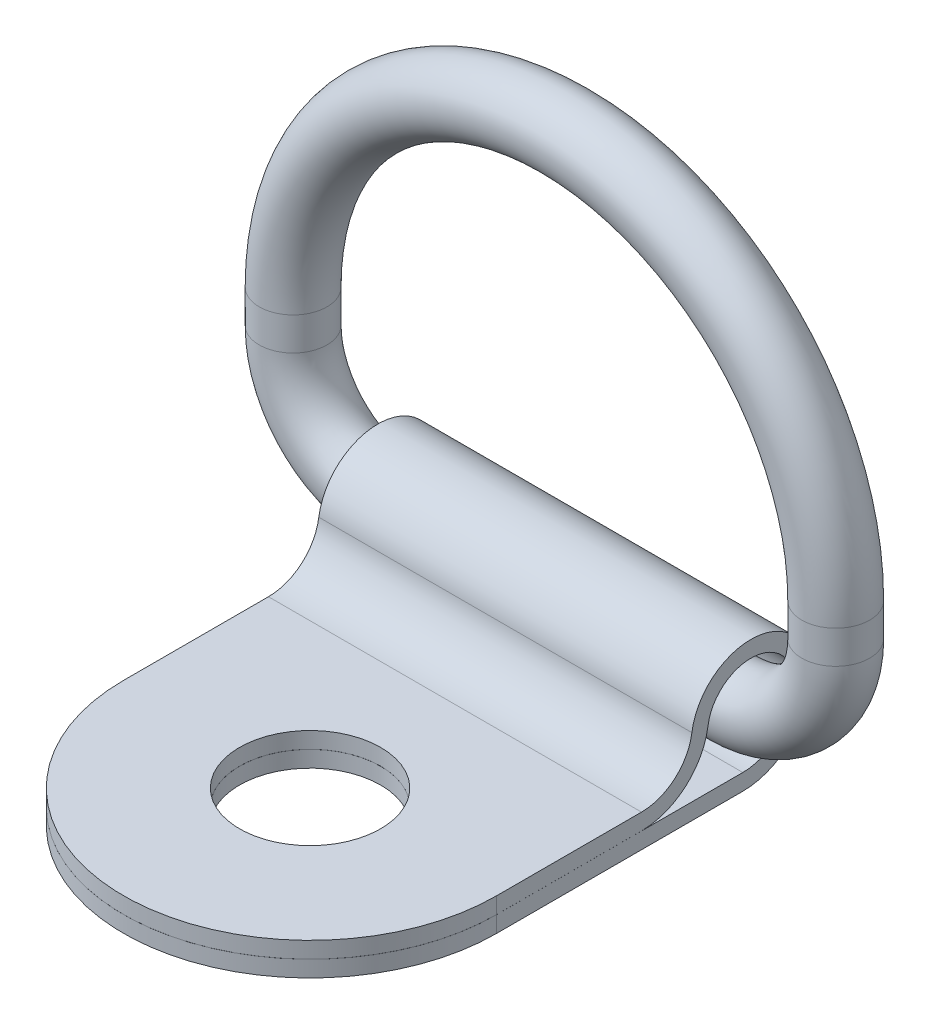
SolidWorks part; units mm, degrees
ref_plane "Front Plane" through (0, 0, 0) normal (0, 0, 1) x (1, 0, 0)
ref_plane "Top Plane" through (0, 0, 0) normal (0, 1, 0) x (1, 0, 0)
ref_plane "Right Plane" through (0, 0, 0) normal (1, 0, 0) x (0, 0, -1)
sketch "Sketch1" plane through (0, 0, 0) normal (0, 0, 1) x (1, 0, 0)
  line L0 (-7.8941, -1.5875) -> (7.8941, -1.5875) construction
  line L1 (0, 0) -> (0, 20.6375) construction
  line L2 (-14.2875, 6.35) -> (-14.2875, 4.8059) construction
  line L3 (-11.1125, 6.35) -> (-11.1125, 4.8059) construction
  line L4 (11.1125, 6.35) -> (11.1125, 4.8059) construction
  line L5 (14.2875, 6.35) -> (14.2875, 4.8059) construction
  line L6 (7.8941, 1.5875) -> (-7.8941, 1.5875) construction
  line L8 (0, 1.5875) -> (0, -1.5875) construction
  line L10 (-12.7, 6.35) -> (-12.7, 4.8059)
  line L11 (12.7, 6.35) -> (12.7, 4.8059)
  line L12 (-7.8941, 0) -> (7.8941, 0)
  arc A0 (14.2875, 6.35) -> (-14.2875, 6.35) centre (0, 6.35) ccw construction
  arc A1 (11.1125, 6.35) -> (-11.1125, 6.35) centre (0, 6.35) ccw construction
  circle A2 centre (0, 19.05) radius 1.5875 construction
  circle A3 centre (0, 0) radius 1.5875 construction
  arc A4 (12.7, 6.35) -> (-12.7, 6.35) centre (0, 6.35) ccw
  arc A5 (-7.8941, 0) -> (-12.7, 4.8059) centre (-7.8941, 4.8059) cw
  arc A6 (7.8941, 0) -> (12.7, 4.8059) centre (7.8941, 4.8059) ccw
  arc A7 (-7.8941, 1.5875) -> (-11.1125, 4.8059) centre (-7.8941, 4.8059) cw construction
  arc A8 (-7.8941, -1.5875) -> (-14.2875, 4.8059) centre (-7.8941, 4.8059) cw construction
  arc A9 (7.8941, -1.5875) -> (14.2875, 4.8059) centre (7.8941, 4.8059) ccw construction
  arc A10 (7.8941, 1.5875) -> (11.1125, 4.8059) centre (7.8941, 4.8059) ccw construction
  dimension "C" = 3.175
  dimension "A" = 22.225
  dimension "B" = 22.225
sketch "Sketch2" plane through (0, 0, 0) normal (1, 0, 0) x (0, 0, -1)
  circle A0 centre (0, 0) radius 1.5875
sweep "Sweep1" add profiles "Sketch2" path "Sketch1"
sketch "Sketch3" plane through (0, 0, 0) normal (1, 0, 0) x (0, 0, -1)
  line L0 (-20.6375, -3.175) -> (-0.381, -3.175)
  line L1 (-20.6375, -3.175) -> (-20.6375, -2.413)
  line L2 (-20.6375, -2.413) -> (-0.381, -2.413)
  line L4 (-20.6375, -2.4105) -> (-20.6375, -1.6485)
  line L5 (-20.6375, -1.6485) -> (-5.1231, -1.6485)
  line L6 (-20.6375, -2.4105) -> (-5.1231, -2.4105)
  line L7 (-11.9062, -3.175) -> (-11.9062, -2.413) construction
  circle A0 centre (0, 0) radius 2.032 construction
  arc A1 (-2.7658, 0.3956) -> (2.794, 0) centre (0, 0) cw
  arc A2 (-2.7658, 0.3956) -> (-5.1231, -1.6485) centre (-5.1231, 0.7328) cw
  arc A3 (-5.1231, -2.4105) -> (-2.0115, 0.2877) centre (-5.1231, 0.7328) ccw
  arc A4 (-2.0115, 0.2877) -> (2.032, 0) centre (0, 0) cw
  arc A5 (-0.381, -2.413) -> (2.032, 0) centre (-0.381, 0) ccw
  arc A6 (-0.381, -3.175) -> (2.794, 0) centre (-0.381, 0) ccw
  dimension "D1" = 4.064
  dimension "D6" = 2.3813
  dimension "D2" = 0.762
  dimension "D3" = 3.175
  dimension "D4" = 20.6375
  dimension "D7" = 0.0025
  dimension "D8" = 11.9062
extrude "Boss-Extrude1" add sketch "Sketch3" along normal mid plane 17.4625 separate body
sketch "Sketch4" plane through (0, -3.175, 0) normal (0, -1, 0) x (1, 0, 0)
  line L0 (-8.7312, 11.9062) -> (-8.7312, 20.6375)
  line L1 (-8.7312, 20.6375) -> (-8.7312, 21.9075)
  line L2 (-8.7312, 21.9075) -> (8.7313, 21.9075)
  line L3 (8.7313, 21.9075) -> (8.7312, 20.6375)
  line L4 (8.7312, 20.6375) -> (8.7312, 11.9062)
  line L5 (8.7312, 20.6375) -> (-8.7312, 20.6375) construction
  line L6 (8.7312, 5.1231) -> (8.7312, 20.6375) construction
  arc A0 (8.7312, 11.9062) -> (-8.7312, 11.9062) centre (0, 11.9062) ccw
  circle A1 centre (0, 11.9062) radius 3.302
  dimension "D3" = 6.604
  dimension "D2" = 1.27
extrude "Cut-Extrude1" cut sketch "Sketch4" against normal through all
sketch "Sketch5" plane through (0, 0, 0) normal (0, 0, 1) x (1, 0, 0)
  line L1 (9.0238, 2.1651) -> (-10.0845, 2.1651)
  line L2 (9.0238, 2.1651) -> (9.0238, -2.2422)
  line L3 (9.0238, -2.2422) -> (-10.0845, -2.2422)
  line L4 (-10.0845, 2.1651) -> (-10.0845, -2.2422)
extrude "Cut-Extrude2" cut sketch "Sketch5" against normal blind 2.54 from offset 2.54 offset against normal yes
